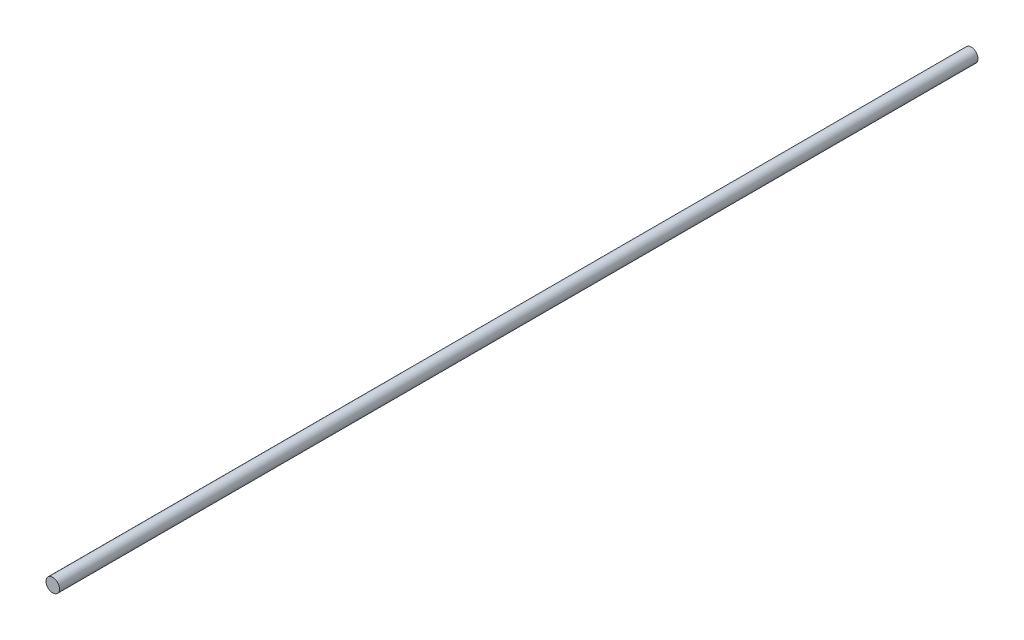
SolidWorks part; units mm, degrees
ref_plane "Płaszczyzna przednia" through (0, 0, 0) normal (0, 0, 1) x (1, 0, 0)
ref_plane "Płaszczyzna górna" through (0, 0, 0) normal (0, 1, 0) x (1, 0, 0)
ref_plane "Płaszczyzna prawa" through (0, 0, 0) normal (1, 0, 0) x (0, 0, -1)
sketch "Szkic1" plane through (0, 0, 0) normal (0, 0, 1) x (1, 0, 0)
  circle A0 centre (0, 0) radius 2.5
  dimension "D1" = 5
extrude "Dodanie-wyciągnięcie1" add sketch "Szkic1" along normal blind 340
